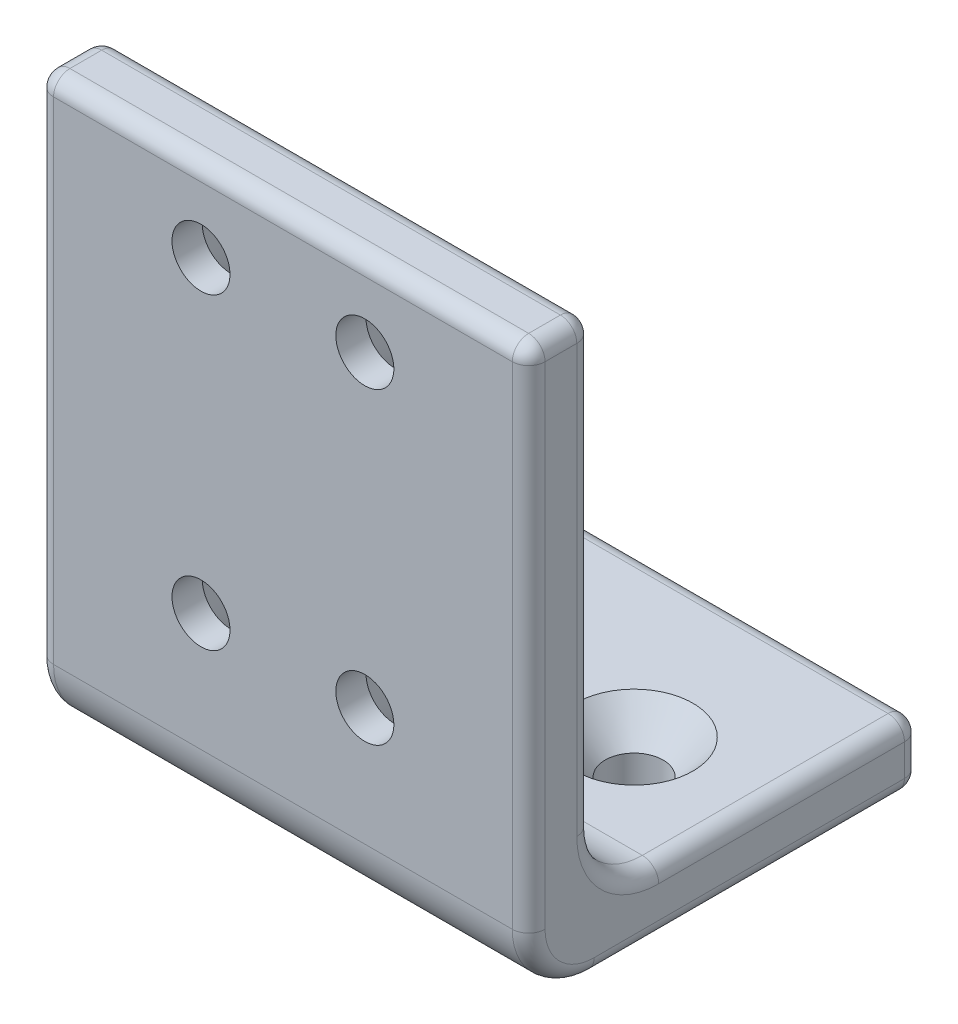
SolidWorks part; units mm, degrees
material "ABS"
ref_plane "Front Plane" through (0, 0, 0) normal (0, 0, 1) x (1, 0, 0)
ref_plane "Top Plane" through (0, 0, 0) normal (0, 1, 0) x (1, 0, 0)
ref_plane "Right Plane" through (0, 0, 0) normal (1, 0, 0) x (0, 0, -1)
sketch "Sketch1" plane through (0, 0, 0) normal (0, 0, 1) x (1, 0, 0)
  line L1 (0, 0) -> (38.1, 0)
  line L2 (0, 0) -> (0, 44.45)
  line L3 (0, 44.45) -> (38.1, 44.45)
  line L4 (38.1, 0) -> (38.1, 44.45)
  dimension "D1" = 38.1
  dimension "D2" = 44.45
extrude "Boss-Extrude1" add sketch "Sketch1" along normal blind 5
sketch "Sketch2" plane through (0, 0, 0) normal (0, 0, -1) x (-1, 0, 0)
  line L0 (0, 44.45) -> (0, 0) construction
  line L1 (-38.1, 0) -> (0, 0)
  line L2 (-38.1, 0) -> (-38.1, 5)
  line L3 (-38.1, 5) -> (0, 5)
  line L4 (0, 0) -> (0, 5)
  dimension "D1" = 5
extrude "Boss-Extrude2" add sketch "Sketch2" along normal blind 25.4
hole_wizard "CSK for #8 Flat Head Socket Cap Screw1" positions "Sketch3" profile "Sketch4" countersink size "#8" standard "ANSI Inch" end condition through all
sketch "Sketch3" plane through (0, 0, 0) normal (0, 0, -1) x (-1, 0, 0)
  line L0 (-38.1, 44.45) -> (0, 44.45) construction
  line L1 (0, 44.45) -> (0, 5) construction
  point P0 (-25.4, 38.1)
  point P2 (-12.7, 38.1)
  point P4 (-12.7, 14.224)
  point P6 (-25.4, 14.224)
  point P13 (0, 0)
  point P14 (0, 0)
  dimension "D1" = 12.7
  dimension "D2" = 12.7
  dimension "D3" = 23.876
  dimension "D4" = 6.35
  dimension "D5" = 12.7
  dimension "D6" = 23.876
  dimension "D7" = 6.35
sketch "Sketch4" plane through (25.4, 38.1, 0) normal (1, 0, 0) x (0, 1, 0)
  line L0 (0, 0) -> (0, 5)
  line L1 (0, 5) -> (2.2479, 5)
  line L2 (2.2479, 5) -> (2.2479, 2.659)
  line L3 (2.2479, 2.659) -> (4.5593, 0)
  line L5 (4.5593, 0) -> (0, 0)
  line L6 (-2.2479, 2.659) -> (-4.5593, 0) construction
  line L11 (0, -6.35) -> (0, 107.95) construction
  dimension "Thru Hole Dia." = 4.4958
  dimension "Thru Hole Depth" = 5
  dimension "Near C'Sink Dia." = 9.1186
  dimension "Near C'Sink Angle" = 82
hole_wizard "CSK for #8 Flat Head Socket Cap Screw2" positions "Sketch5" profile "Sketch6" countersink size "#8" standard "ANSI Inch" end condition through all
sketch "Sketch5" plane through (0, 5, 0) normal (0, 1, 0) x (1, 0, 0)
  line L0 (0, 25.4) -> (38.1, 25.4) construction
  line L1 (38.1, 25.4) -> (38.1, 0) construction
  point P0 (28.575, 12.7)
  point P2 (9.525, 12.7)
  dimension "D1" = 12.7
  dimension "D2" = 12.7
  dimension "D3" = 19.05
  dimension "D4" = 9.525
sketch "Sketch6" plane through (28.575, 5, -12.7) normal (1, 0, 0) x (0, 0, 1)
  line L0 (0, 0) -> (0, 5)
  line L1 (0, 5) -> (2.2479, 5)
  line L2 (2.2479, 5) -> (2.2479, 2.659)
  line L3 (2.2479, 2.659) -> (4.5593, 0)
  line L5 (4.5593, 0) -> (0, 0)
  line L6 (-2.2479, 2.659) -> (-4.5593, 0) construction
  line L11 (0, -6.35) -> (0, 107.95) construction
  dimension "Thru Hole Dia." = 4.4958
  dimension "Thru Hole Depth" = 5
  dimension "Near C'Sink Dia." = 9.1186
  dimension "Near C'Sink Angle" = 82
fillet "Fillet1" radius 5.08 1 edges at (19.05, 5, 0)
fillet "Fillet2" radius 5.08 1 edges at (19.05, 0, 5)
fillet "Fillet3" radius 1.27 20 edges at (38.1, 44.45, 2.5) (38.1, 27.265, 0) (38.1, 6.4879, -1.4879) (38.1, 5, -15.24) (38.1, 0, -12.74) (38.1, 1.4879, 3.5121) (38.1, 24.765, 5) (19.05, 5, -25.4) (19.05, 0, -25.4) (38.1, 2.5, -25.4) (0, 2.5, -25.4) (0, 5, -15.24) (0, 6.4879, -1.4879) (0, 27.265, 0) (0, 44.45, 2.5) (0, 24.765, 5) (0, 1.4879, 3.5121) (0, 0, -12.74) (19.05, 44.45, 5) (19.05, 44.45, 0)
